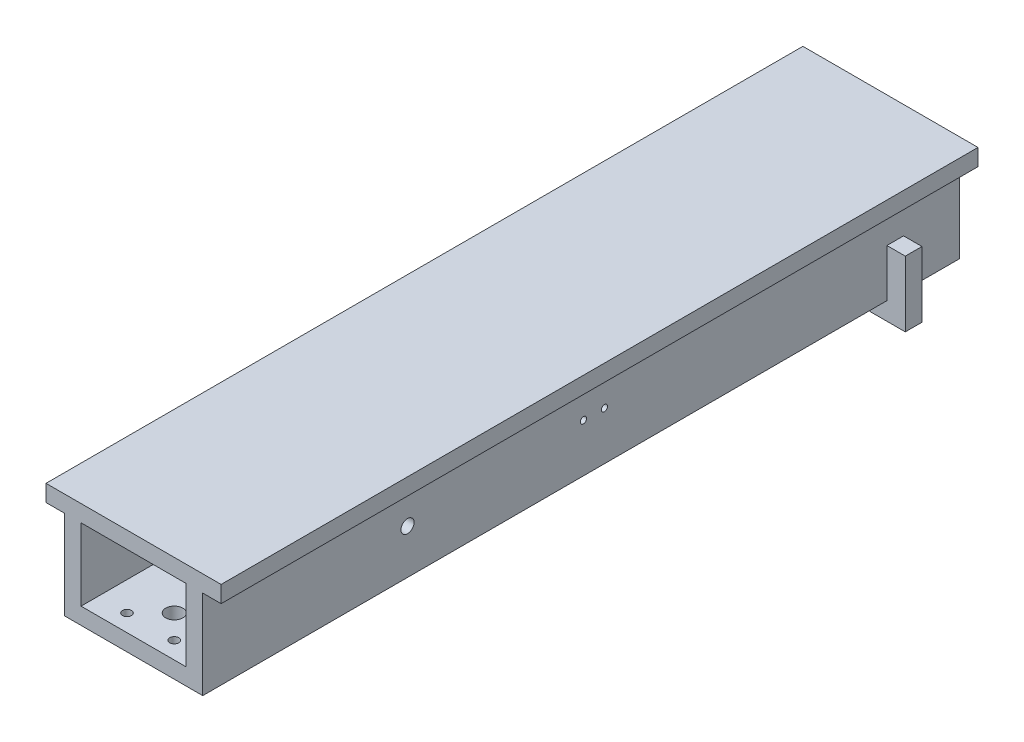
SolidWorks part; units mm, degrees
ref_plane "Front Plane" through (0, 0, 0) normal (0, 0, 1) x (1, 0, 0)
ref_plane "Top Plane" through (0, 0, 0) normal (0, 1, 0) x (1, 0, 0)
ref_plane "Right Plane" through (0, 0, 0) normal (1, 0, 0) x (0, 0, -1)
sketch "Sketch1" plane through (0, 0, 0) normal (0, 0, 1) x (1, 0, 0)
  line L0 (-6.35, 33.85) -> (46.35, 33.85)
  line L1 (0, 0) -> (40, 0)
  line L2 (0, 0) -> (0, 27.5)
  line L3 (0, 27.5) -> (40, 27.5)
  line L4 (40, 0) -> (40, 27.5)
  line L5 (46.35, -6.35) -> (46.35, 33.85)
  line L6 (-6.35, -6.35) -> (46.35, -6.35)
  line L7 (-6.35, -6.35) -> (-6.35, 33.85)
  dimension "D1" = 40
  dimension "D2" = 27.5
  dimension "D3" = 6.35
extrude "Boss-Extrude1" add sketch "Sketch1" along normal blind 46
sketch "Sketch2" plane through (0, -6.35, 0) normal (0, -1, 0) x (1, 0, 0)
  line L1 (20, 30.5) -> (-6.35, 46) construction
  line L2 (20, 30.5) -> (46.35, 46) construction
  line L3 (-6.35, 46) -> (46.35, 46) construction
  circle A0 centre (29, 39.5) radius 1.7
  circle A1 centre (11, 39.5) radius 1.7
  circle A2 centre (11, 6.5) radius 1.7
  circle A3 centre (29, 6.5) radius 1.7
  circle A4 centre (20, 30.5) radius 3.25
  line B0 (5, 46) -> (35, 46)
  circle B1 centre (11, 6.5) radius 3.5
  circle B2 centre (29, 6.5) radius 3.5
  circle B3 centre (29, 39.5) radius 3.5
  circle B4 centre (11, 39.5) radius 3.5
  circle B5 centre (20, 30.5) radius 6.25
  dimension "D1" = 3.4
  dimension "D2" = 6.5
sketch_block_instance "DC_Motor_Mount-1"
sketch_block "DC_Motor_Mount"
extrude "Cut-Extrude1" cut sketch "Sketch2" along direction (0, 1, 0) on the side against the normal up to surface (6.35 mm away) contours A4 | A2 | A3 | A1 | A0
sketch "Sketch3" plane through (0, 0, 0) normal (0, 0, -1) x (-1, 0, 0)
  line L14 (6.35, 33.85) -> (6.35, -13.15)
  line L15 (6.35, 33.85) -> (-46.35, 33.85)
  line L16 (-46.35, 33.85) -> (-46.35, -13.15)
  line L17 (-46.35, -13.15) -> (-40, -13.15)
  line L19 (6.35, -13.15) -> (0, -13.15)
  line L26 (-40, 27.5) -> (0, 27.5) construction
  line L30 (-40, 27.5) -> (0, 27.5)
  line L31 (0, 27.5) -> (0, -13.15)
  line L32 (-40, 27.5) -> (-40, -13.15)
  dimension "D1" = 47
  dimension "D2" = 47
extrude "Boss-Extrude2" add sketch "Sketch3" along normal offset from surface (242.29 mm away) 288.29 up to face at (20, 13.75, 46)
sketch "Sketch4" plane through (-6.35, 0, 0) normal (-1, 0, 0) x (0, 0, 1)
  line L0 (46, 33.85) -> (46, -6.35) construction
  line L1 (-242.29, 33.85) -> (46, 33.85)
  line L2 (-242.29, 33.85) -> (-242.29, 27.5)
  line L3 (-242.29, 27.5) -> (46, 27.5)
  line L4 (46, 33.85) -> (46, 27.5)
  dimension "D1" = 6.35
extrude "Boss-Extrude3" add sketch "Sketch4" along normal blind 7
sketch "Sketch5" plane through (-6.35, 0, 0) normal (-1, 0, 0) x (0, 0, 1)
  line L1 (-138.145, 23.75) -> (-138.145, 3.75) construction
  line L2 (-138.145, 3.75) -> (-118.145, 3.75) construction
  line L3 (-118.145, 3.75) -> (-118.145, 23.75) construction
  line L4 (-118.145, 23.75) -> (-138.145, 23.75) construction
  line L5 (-138.145, 13.75) -> (-242.29, 13.75) construction
  point P17 (-98.145, 27.5)
  line B0 (0, 0) -> (46, 0)
  line B1 (46, 27.5) -> (-242.29, 27.5)
  line B2 (-242.29, 27.5) -> (-242.29, 0)
  line B3 (-242.29, 0) -> (0, 0)
  line B4 (46, 0) -> (46, 27.5)
  circle B5 centre (-138.145, 3.75) radius 1.7
  circle B6 centre (-118.145, 3.75) radius 1.7
  circle B7 centre (-118.145, 23.75) radius 1.7
  circle B8 centre (-138.145, 23.75) radius 1.7
  dimension "D5" = 20
sketch_block_instance "Block1-1"
sketch_block "Block1" parameters "D1"=3.4, "D2"=20, "D3"=20
sketch "Sketch6" plane through (46.35, 0, 0) normal (1, 0, 0) x (0, 0, -1)
  line L1 (-46, 33.85) -> (242.29, 33.85)
  line L2 (-46, 33.85) -> (-46, 27.5)
  line L3 (-46, 27.5) -> (242.29, 27.5)
  line L4 (242.29, 33.85) -> (242.29, 27.5)
  line L5 (242.29, 33.85) -> (242.29, -13.15) construction
  dimension "D1" = 6.35
extrude "Boss-Extrude4" add sketch "Sketch6" along normal blind 7
sketch "Sketch7" plane through (46.35, 0, 0) normal (1, 0, 0) x (0, 0, -1)
  line L0 (242.29, -13.15) -> (0, -13.15) construction
  line L1 (220.94, -13.15) -> (214.59, -13.15)
  line L2 (220.94, -13.15) -> (220.94, 11.85)
  line L3 (220.94, 11.85) -> (214.59, 11.85)
  line L4 (214.59, -13.15) -> (214.59, 11.85)
  line L5 (242.29, 27.5) -> (242.29, -13.15) construction
  dimension "D1" = 21.35
  dimension "D2" = 6.35
  dimension "D3" = 25
extrude "Boss-Extrude5" add sketch "Sketch7" along normal up to surface (7 mm away) up to face at (53.35, 30.675, -98.145)
ref_plane "Plane1" through (40, 27.5, -242.29) normal (-1, 0, 0) x (0, 0, 1)
sketch "Sketch9" plane through (40, 27.5, -242.29) normal (-1, 0, 0) x (0, 0, 1)
  line L0 (288.29, 0) -> (288.29, -33.85) construction
  line L1 (210.29, -16.925) -> (288.29, -16.925) construction
  circle A0 centre (210.29, -16.925) radius 2.5
  dimension "D2" = 5
  dimension "D1" = 78
extrude "Cut-Extrude2" cut sketch "Sketch9" against normal up to surface and the other way up to surface up to face at (46.35, 1.34, -126.364) other way up to face at (-6.35, 2.6667, -65.43)
sketch "Sketch10" plane through (46.35, 0, 0) normal (1, 0, 0) x (0, 0, -1)
  line L0 (-46, -6.35) -> (-46, 27.5) construction
  line L1 (99, 24) -> (107, 24) construction
  line L2 (99, 24) -> (99, 12) construction
  line L3 (99, 12) -> (107, 12) construction
  line L4 (107, 24) -> (107, 12) construction
  line L5 (-46, 27.5) -> (242.29, 27.5) construction
  line L7 (99, 24) -> (103, 24) construction
  line L8 (99, 24) -> (99, 18) construction
  line L9 (99, 18) -> (103, 18) construction
  line L10 (103, 24) -> (103, 18) construction
  circle A0 centre (99, 24) radius 1.2
  circle A1 centre (99, 12) radius 1.2
  circle A2 centre (107, 12) radius 1.2
  circle A3 centre (107, 24) radius 1.2
  point P10 (107, 18)
  point P13 (103, 18)
  point P19 (103, 24)
  point P22 (99, 18)
  dimension "D3" = 2.4
  dimension "D1" = 12
  dimension "D2" = 8
  dimension "D4" = 145
  dimension "D5" = 9.5
extrude "Cut-Extrude3" cut sketch "Sketch10" against normal up to surface (52.7 mm away) up to face at (-6.35, 10.575, -34.5)
sketch "Sketch11" plane through (46.35, 0, 0) normal (1, 0, 0) x (0, 0, -1)
  line L0 (220.94, -13.15) -> (220.94, 11.85) construction
  line L1 (242.29, -13.15) -> (220.94, -13.15)
  line L2 (242.29, -13.15) -> (242.29, -6.35)
  line L3 (242.29, -6.35) -> (220.94, -6.35)
  line L4 (220.94, -13.15) -> (220.94, -6.35)
  line L5 (0, -6.35) -> (0, -13.15) construction
  line L6 (214.59, -13.15) -> (0, -13.15)
  line L7 (214.59, -13.15) -> (214.59, -6.35)
  line L8 (214.59, -6.35) -> (0, -6.35)
  line L9 (0, -13.15) -> (0, -6.35)
  point P14 (0, -9.75)
  dimension "D1" = 6.8
  dimension "D2" = 6.8
extrude "Cut-Extrude4" cut sketch "Sketch11" against normal up to surface (52.7 mm away) up to face at (-6.35, 24, -108.2)
sketch "Sketch12" plane through (0, -13.15, 0) normal (0, -1, 0) x (1, 0, 0)
  line L4 (-6.35, -214.59) -> (-6.35, -220.94)
  line L5 (-6.35, -220.94) -> (0, -220.94)
  line L6 (0, -220.94) -> (0, -214.59)
  line L7 (0, -214.59) -> (-6.35, -214.59)
  line L8 (-6.35, -214.59) -> (-6.35, -220.94)
  line L9 (-6.35, -220.94) -> (0, -220.94)
  line L10 (0, -220.94) -> (0, -214.59)
  line L11 (0, -214.59) -> (-6.35, -214.59)
  dimension "D1" = 0
extrude "Cut-Extrude5" cut sketch "Sketch12" against normal up to surface (6.8 mm away) up to face at (-3.175, -6.35, -231.615)
sketch "Right Side"
sketch_block_instance "Block2-1"
sketch_block "Block2" parameters "D3"=3.5719, "D1"=6.35, "D2"=33.3, "D4"=3.175
sketch "Top"
sketch_block_instance "Block3-1"
sketch_block "Block3" parameters "D1"=3.5719
sketch "Left Side"
sketch_block_instance "Block4-1"
sketch_block "Block4" parameters "D1"=3.5719
sketch "L" plane through (0, 0, -220.94) normal (0, 0, -1) x (-1, 0, 0)
  line B0 (-53.35, -13.15) -> (-40, -13.15)
  line B1 (-40, -13.15) -> (-40, -6.35)
  line B2 (-40, -6.35) -> (-46.35, -6.35)
  line B3 (-46.35, -6.35) -> (-46.35, 11.85)
  line B4 (-46.35, 11.85) -> (-53.35, 11.85)
  line B5 (-53.35, 11.85) -> (-53.35, -13.15)
sketch_block_instance "Block5-1"
sketch_block "Block5"
sketch "Sketch13" plane through (0, 0, 0) normal (0, 1, 0) x (1, 0, 0)
  line B0 (32, 0) -> (0, 0)
  line B1 (0, 0) -> (0, -46)
  line B2 (0, -46) -> (32, -46)
  line B3 (32, -46) -> (32, 0)
  circle B4 centre (25, -39.5) radius 1.7
  circle B5 centre (7, -39.5) radius 1.7
  circle B6 centre (25, -6.5) radius 1.7
  circle B7 centre (7, -6.5) radius 1.7
  circle B8 centre (16, -30.5) radius 3.25
sketch_block_instance "Block6-1"
sketch_block "Block6"
